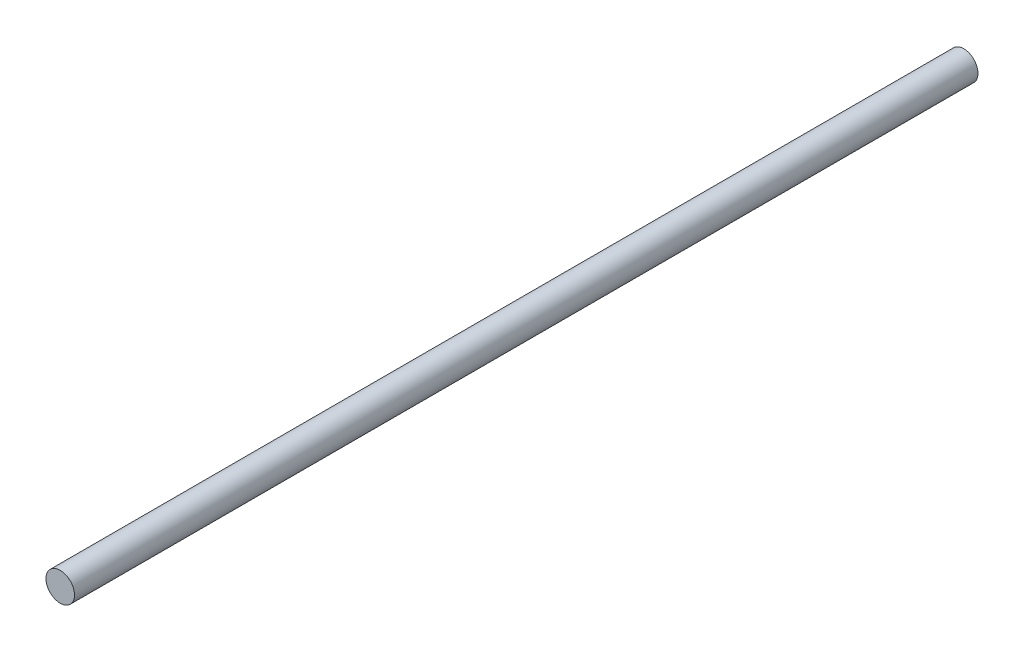
SolidWorks part; units mm, degrees
ref_plane "Plan de face" through (0, 0, 0) normal (0, 0, 1) x (1, 0, 0)
ref_plane "Plan de dessus" through (0, 0, 0) normal (0, 1, 0) x (1, 0, 0)
ref_plane "Plan de droite" through (0, 0, 0) normal (1, 0, 0) x (0, 0, -1)
sketch "Esquisse1" plane through (0, 0, 0) normal (0, 0, 1) x (1, 0, 0)
  circle A0 centre (0, 0) radius 1.5
  dimension "D1" = 3
extrude "Boss.-Extru.1" add sketch "Esquisse1" along normal blind 95
